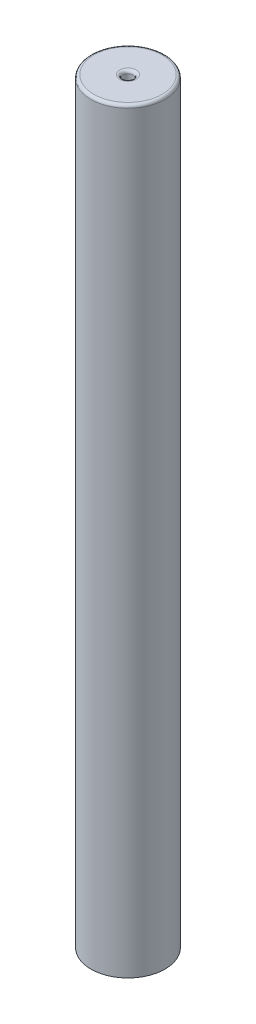
SolidWorks part; units mm, degrees
material "CK45"
ref_plane "Front Plane" through (0, 0, 0) normal (0, 0, 1) x (1, 0, 0)
ref_plane "Top Plane" through (0, 0, 0) normal (0, 1, 0) x (1, 0, 0)
ref_plane "Right Plane" through (0, 0, 0) normal (1, 0, 0) x (0, 0, -1)
sketch "Sketch1" plane through (0, 0, 0) normal (0, 1, 0) x (1, 0, 0)
  circle A0 centre (0, 0) radius 25
  dimension "D1" = 50
extrude "Boss-Extrude1" add sketch "Sketch1" along normal blind 510
sketch "Sketch2" plane through (0, 510, 0) normal (0, 1, 0) x (1, 0, 0)
  circle A0 centre (0, 0) radius 3.5
  dimension "D1" = 7
extrude "Cut-Extrude1" cut sketch "Sketch2" against normal blind 30
fillet "Fillet1" radius 2 2 edges at (0, 510, 3.5) (0, 510, 25)
